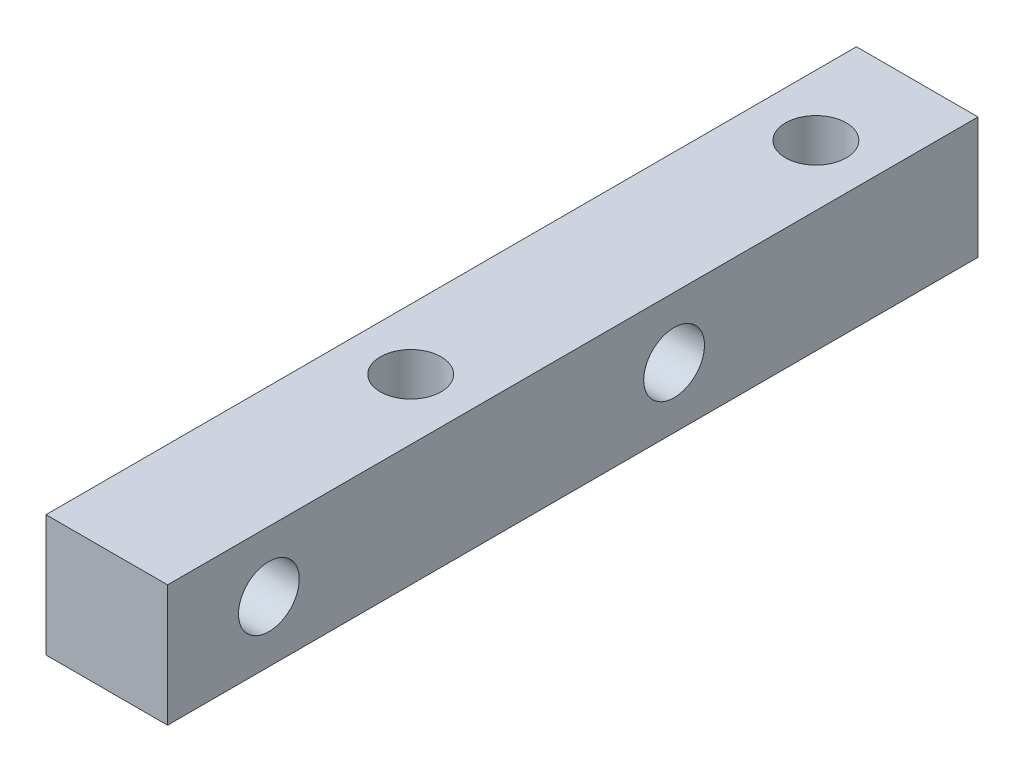
SolidWorks part; units mm, degrees
ref_plane "前视基准面" through (0, 0, 0) normal (0, 0, 1) x (1, 0, 0)
ref_plane "上视基准面" through (0, 0, 0) normal (0, 1, 0) x (1, 0, 0)
ref_plane "右视基准面" through (0, 0, 0) normal (1, 0, 0) x (0, 0, -1)
other "Configuration Table"
sketch "草图1" plane through (0, 0, 0) normal (0, 0, 1) x (1, 0, 0)
  line L1 (-3, -3) -> (3, -3)
  line L2 (-3, -3) -> (-3, 3)
  line L3 (-3, 3) -> (3, 3)
  line L4 (3, -3) -> (3, 3)
  line L5 (-3, -3) -> (3, 3) construction
  line L6 (-3, 3) -> (3, -3) construction
  point P0 (0, 0)
  dimension "D1" = 6
extrude "凸台-拉伸1" add sketch "草图1" along normal mid plane 40
sketch "草图2" plane through (3, 0, 0) normal (1, 0, 0) x (0, 0, -1)
  line L0 (-20, -3) -> (-20, 3) construction
  circle A0 centre (-15, 0) radius 1.5
  circle A1 centre (5, 0) radius 1.5
  dimension "D1" = 20
  dimension "D3" = 3
  dimension "D2" = 5
extrude "切除-拉伸1" cut sketch "草图2" against normal through all
cosmetic thread "装饰螺纹线3" parameters "D2"=4.2556
cosmetic thread "装饰螺纹线4" parameters "D2"=4.2556
sketch "草图3" plane through (0, 3, 0) normal (0, 1, 0) x (1, 0, 0)
  line L0 (3, 20) -> (-3, 20) construction
  circle A0 centre (0, 15) radius 1.5
  circle A1 centre (0, -5) radius 1.5
  dimension "D1" = 3
  dimension "D2" = 20
  dimension "D3" = 5
extrude "切除-拉伸2" cut sketch "草图3" against normal through all
cosmetic thread "装饰螺纹线1" parameters "D2"=4
cosmetic thread "装饰螺纹线2" parameters "D2"=4
